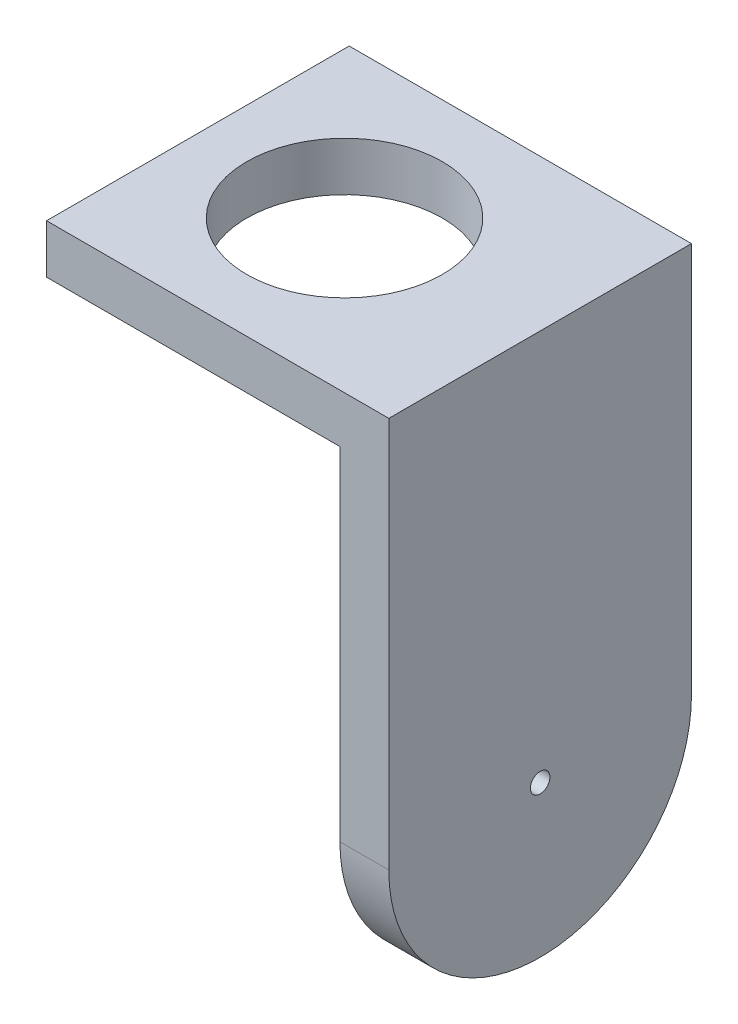
SolidWorks part; units mm, degrees
ref_plane "Front Plane" through (0, 0, 0) normal (0, 0, 1) x (1, 0, 0)
ref_plane "Top Plane" through (0, 0, 0) normal (0, 1, 0) x (1, 0, 0)
ref_plane "Right Plane" through (0, 0, 0) normal (1, 0, 0) x (0, 0, -1)
sketch "Sketch3" plane through (0, 0, 0) normal (1, 0, 0) x (0, 0, -1)
  line L0 (15.4731, -60.9318) -> (-15.4731, -60.9318)
  line L2 (15.4731, -60.9318) -> (15.4731, -100.9318)
  line L4 (-15.4731, -60.9318) -> (-15.4731, -100.9318)
  line L6 (11.2945, -90.3558) -> (7.6165, -60.9318) construction
  line L8 (-7.6165, -60.9318) -> (-11.2945, -90.3558) construction
  arc A0 (-15.4731, -100.9318) -> (15.4731, -100.9318) centre (0, -100.9318) ccw
  point P0 (0, 0)
  point P5 (0, -100.9318)
  dimension "D1" = 40
extrude "Boss-Extrude2" add sketch "Sketch3" along normal blind 5
sketch "Sketch5" plane through (0, 0, 0) normal (-1, 0, 0) x (0, 0, 1)
  circle A0 centre (0, -100.9318) radius 1
  arc A5 (-15.4731, -100.9318) -> (15.4731, -100.9318) centre (0, -100.9318) ccw construction
  dimension "D1" = 0
  dimension "D2" = 2
extrude "Cut-Extrude2" cut sketch "Sketch5" against normal blind 5
sketch "Sketch6" plane through (0, 0, 0) normal (-1, 0, 0) x (0, 0, 1)
  line L0 (15.4731, -60.9318) -> (15.4731, -100.9318) construction
  line L1 (-15.4731, -60.9318) -> (15.4731, -60.9318)
  line L2 (-15.4731, -60.9318) -> (-15.4731, -65.9318)
  line L3 (-15.4731, -65.9318) -> (15.4731, -65.9318)
  line L4 (15.4731, -60.9318) -> (15.4731, -65.9318)
  dimension "D1" = 5
extrude "Boss-Extrude3" add sketch "Sketch6" along normal blind 30
sketch "Sketch10" plane through (0, -65.9318, 0) normal (0, -1, 0) x (1, 0, 0)
  line L0 (-30, -15.4731) -> (-30, 15.4731) construction
  circle A0 centre (-15, 0) radius 10
  dimension "D1" = 20
  dimension "D2" = 15
extrude "Cut-Extrude3" cut sketch "Sketch10" against normal blind 30
